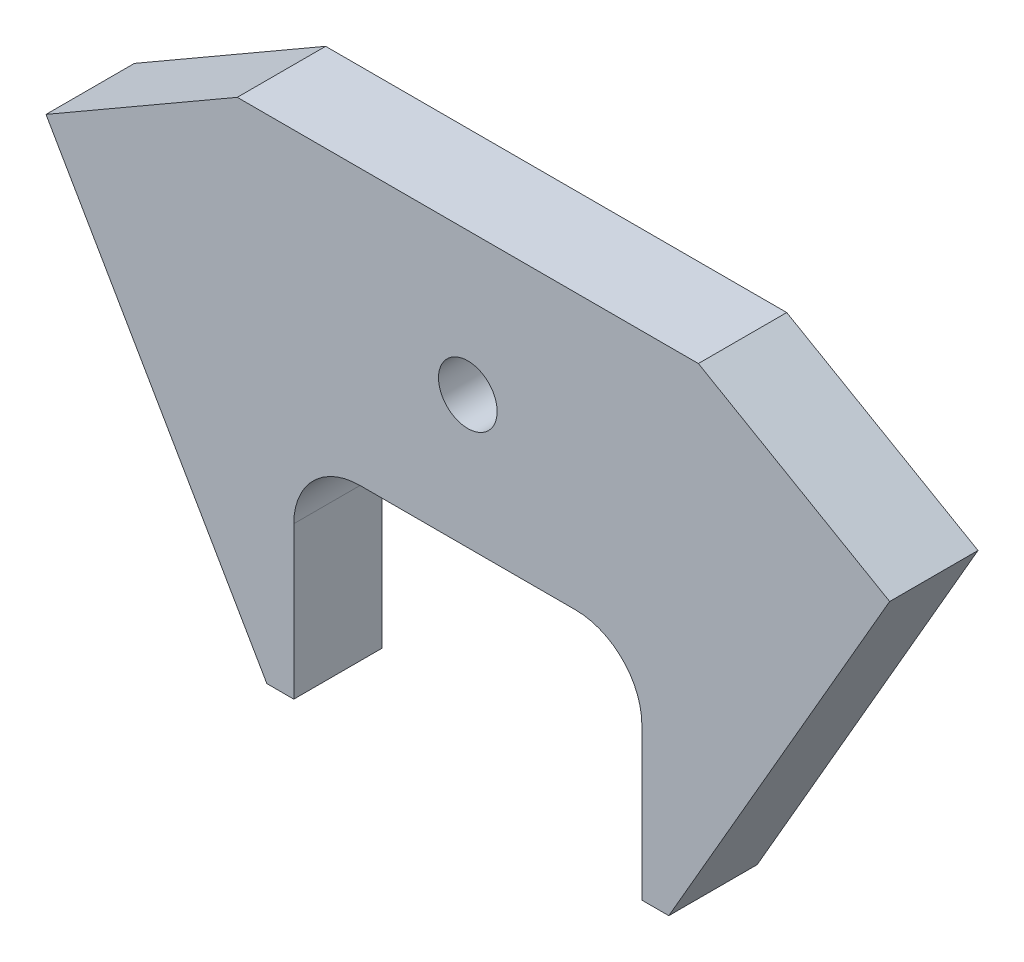
SolidWorks part; units mm, degrees
ref_plane "Front" through (0, 0, 0) normal (0, 0, 1) x (1, 0, 0)
ref_plane "Top" through (0, 0, 0) normal (0, 1, 0) x (1, 0, 0)
ref_plane "Right" through (0, 0, 0) normal (1, 0, 0) x (0, 0, -1)
sketch "Sketch1" plane through (0, 0, 0) normal (0, 0, 1) x (1, 0, 0)
  line L0 (25.019, 0) -> (28.8895, 0)
  line L1 (28.8895, 0) -> (60.6395, 54.9926)
  line L2 (-25.019, 0) -> (25.019, 0) construction
  line L3 (-60.6395, 54.9926) -> (60.6395, 54.9926) construction
  line L4 (-60.6395, 54.9926) -> (-33.1431, 70.8676)
  line L5 (-33.1431, 70.8676) -> (33.1431, 70.8676)
  line L6 (33.1431, 70.8676) -> (60.6395, 54.9926)
  line L7 (-25.019, 0) -> (-28.8895, 0)
  line L8 (-28.8895, 0) -> (-60.6395, 54.9926)
  line L9 (-25.019, 0) -> (-25.019, 31.369)
  line L10 (-25.019, 31.369) -> (25.019, 31.369)
  line L11 (25.019, 31.369) -> (25.019, 0)
  line L12 (0, 70.8676) -> (0, 50.419) construction
  line L13 (0, 50.419) -> (0, 31.369) construction
  circle A1 centre (0, 0) radius 25.019 construction
  point P9 (0, 25.019)
  dimension "D1" = 50.038
  dimension "D6" = 6.35
  dimension "D2" = 63.5
  dimension "D3" = 180
  dimension "D4" = 60
  dimension "D5" = 31.75
  dimension "D7" = 19.05
extrude "Boss-Extrude1" add sketch "Sketch1" along normal blind 12.7
fillet "Fillet1" radius 9.525 2 edges at (25.019, 31.369, 6.35) (-25.019, 31.369, 6.35)
hole_wizard "5/16 Clearance Hole1" positions "Sketch3" profile "Sketch2" hole size "5/16" standard "ANSI Inch" end condition through all
sketch "Sketch3" plane through (0, 0, 0) normal (0, 0, -1) x (-1, 0, 0)
  point P0 (0, 50.419)
sketch "Sketch2" plane through (0, 50.419, 0) normal (1, 0, 0) x (0, 1, 0)
  line L0 (0, 0) -> (0, 12.7)
  line L1 (0, 12.7) -> (4.2164, 12.7)
  line L2 (4.2164, 12.7) -> (4.2164, 0)
  line L5 (4.2164, 0) -> (0, 0)
  line L11 (0, -6.35) -> (0, 107.95) construction
  dimension "Thru Hole Dia." = 8.4328
  dimension "Thru Hole Depth" = 12.7
